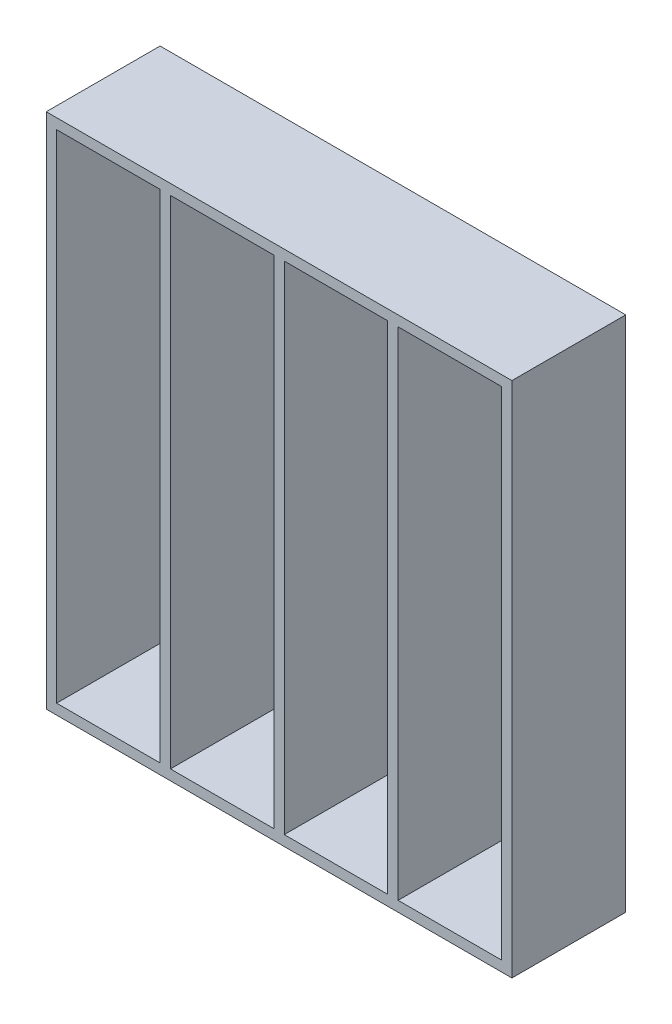
SolidWorks part; units mm, degrees
ref_plane "Plan de face" through (0, 0, 0) normal (0, 0, 1) x (1, 0, 0)
ref_plane "Plan de dessus" through (0, 0, 0) normal (0, 1, 0) x (1, 0, 0)
ref_plane "Plan de droite" through (0, 0, 0) normal (1, 0, 0) x (0, 0, -1)
sketch "Esquisse1" plane through (0, 0, 0) normal (0, 0, 1) x (1, 0, 0)
  line L1 (0, 0) -> (-45, 0)
  line L2 (0, 0) -> (0, 50)
  line L3 (0, 50) -> (-45, 50)
  line L4 (-45, 0) -> (-45, 50)
  dimension "D1" = 50
  dimension "D2" = 45
extrude "Extrusion1" add sketch "Esquisse1" along normal blind 11
sketch "Esquisse2" plane through (0, 0, 11) normal (0, 0, 1) x (1, 0, 0)
  line L0 (-45, 50) -> (-45, 0) construction
  line L1 (-44, 49) -> (-34, 49)
  line L2 (-44, 49) -> (-44, 1)
  line L3 (-44, 1) -> (-34, 1)
  line L4 (-34, 49) -> (-34, 1)
  line L5 (-33, 49) -> (-23, 49)
  line L6 (-33, 49) -> (-33, 1)
  line L7 (-33, 1) -> (-23, 1)
  line L8 (-23, 49) -> (-23, 1)
  line L9 (-22, 49) -> (-12, 49)
  line L10 (-22, 49) -> (-22, 1)
  line L11 (-22, 1) -> (-12, 1)
  line L12 (-12, 49) -> (-12, 1)
  line L13 (-11, 49) -> (-1, 49)
  line L14 (-11, 49) -> (-11, 1)
  line L15 (-11, 1) -> (-1, 1)
  line L16 (-1, 49) -> (-1, 1)
  line L17 (-45, 0) -> (0, 0) construction
  line L18 (0, 50) -> (-45, 50) construction
  dimension "D1" = 1
  dimension "D2" = 1
  dimension "D3" = 1
  dimension "D4" = 10
  dimension "D5" = 1
  dimension "D6" = 1
  dimension "D7" = 1
  dimension "D8" = 1
  dimension "D9" = 1
  dimension "D10" = 1
  dimension "D11" = 1
  dimension "D12" = 1
  dimension "D13" = 1
  dimension "D14" = 10
  dimension "D15" = 10
  dimension "D16" = 10
extrude "Enlèv. mat.-Extru.1" cut sketch "Esquisse2" against normal blind 10
